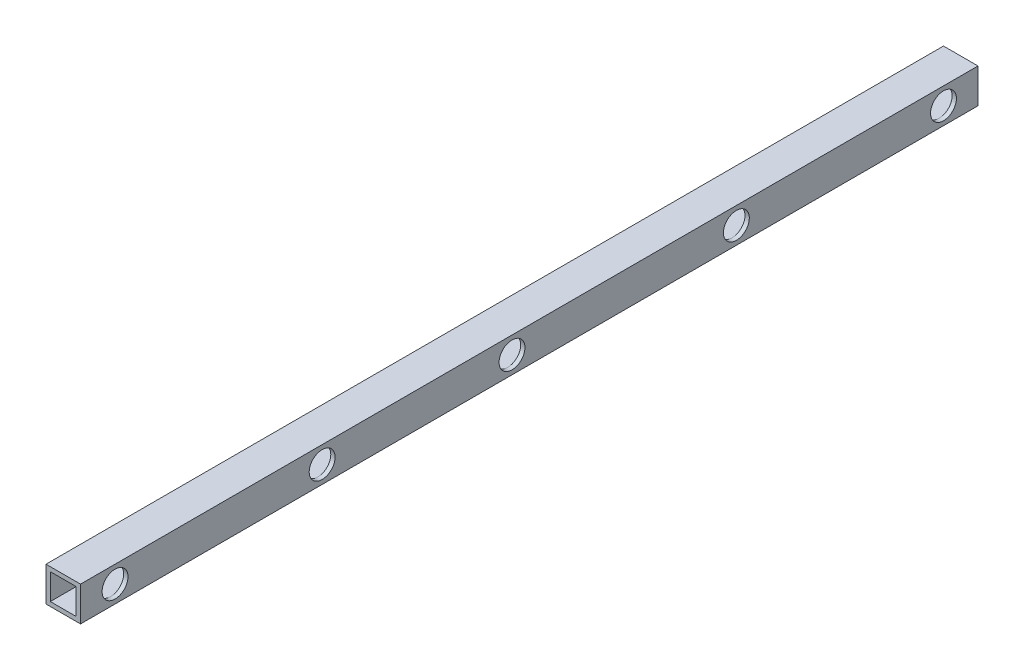
SolidWorks part; units mm, degrees
material "6061 Alloy"
ref_plane "Front" through (0, 0, 0) normal (0, 0, 1) x (1, 0, 0)
ref_plane "Top" through (0, 0, 0) normal (0, 1, 0) x (1, 0, 0)
ref_plane "Right" through (0, 0, 0) normal (1, 0, 0) x (0, 0, -1)
sketch "Sketch1" plane through (0, 0, 0) normal (0, 0, 1) x (1, 0, 0)
  line L1 (0, 0) -> (-25.4, 0)
  line L2 (0, 0) -> (0, 25.4)
  line L3 (0, 25.4) -> (-25.4, 25.4)
  line L4 (-25.4, 0) -> (-25.4, 25.4)
  dimension "D1" = 25.4
extrude "Extrude-Thin1" add sketch "Sketch1" along normal blind 660.4 thin
sketch "Sketch2" plane through (-25.4, 0, 0) normal (-1, 0, 0) x (0, 0, 1)
  line L0 (660.4, 25.4) -> (0, 25.4) construction
  line L1 (0, 25.4) -> (0, 0) construction
  line L2 (660.4, 25.4) -> (660.4, 0) construction
  circle A0 centre (25.4, 12.7) radius 9.525
  circle A1 centre (177.8, 12.7) radius 9.525
  circle A2 centre (482.6, 12.7) radius 9.525
  circle A3 centre (635, 12.7) radius 9.525
  circle A4 centre (342.9, 12.7) radius 9.525
  point P16 (660.4, 12.7)
  point P17 (0, 0)
  dimension "D1" = 19.05
  dimension "D2" = 12.7
  dimension "D3" = 25.4
  dimension "D4" = 177.8
  dimension "D5" = 25.4
  dimension "D6" = 177.8
  dimension "D7" = 317.5
extrude "Cut-Extrude1" cut sketch "Sketch2" against normal through all
equation "\"D5@Sketch2\"=\"D3@Sketch2\""
equation "\"D6@Sketch2\"=\"D4@Sketch2\""
